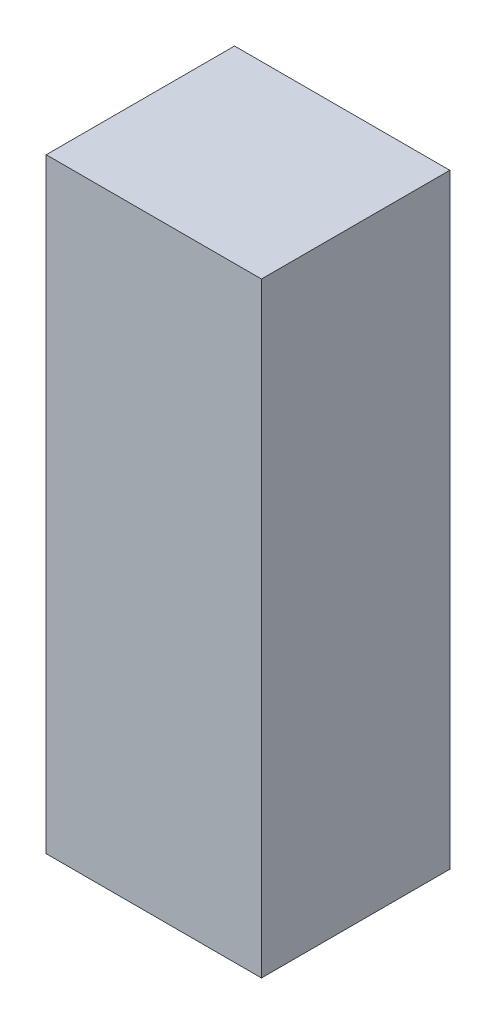
SolidWorks part; units mm, degrees
ref_plane "Front Plane" through (0, 0, 0) normal (0, 0, 1) x (1, 0, 0)
ref_plane "Top Plane" through (0, 0, 0) normal (0, 1, 0) x (1, 0, 0)
ref_plane "Right Plane" through (0, 0, 0) normal (1, 0, 0) x (0, 0, -1)
sketch "Sketch1" plane through (0, 0, 0) normal (0, 1, 0) x (1, 0, 0)
  line L1 (-34.9934, 25.4598) -> (-14.6734, 25.4598)
  line L2 (-34.9934, 25.4598) -> (-34.9934, 43.2398)
  line L3 (-34.9934, 43.2398) -> (-14.6734, 43.2398)
  line L4 (-14.6734, 25.4598) -> (-14.6734, 43.2398)
  line L5 (-34.9934, 25.4598) -> (-14.6734, 43.2398) construction
  line L6 (-34.9934, 43.2398) -> (-14.6734, 25.4598) construction
  point P0 (-24.8334, 34.3498)
  point P6 (0, 0)
  point P7 (0, 0)
  point P12 (0, 0)
  point P13 (0, 0)
  dimension "D1" = 20.32
  dimension "D2" = 17.78
extrude "Boss-Extrude1" add sketch "Sketch1" along normal blind 57.15
